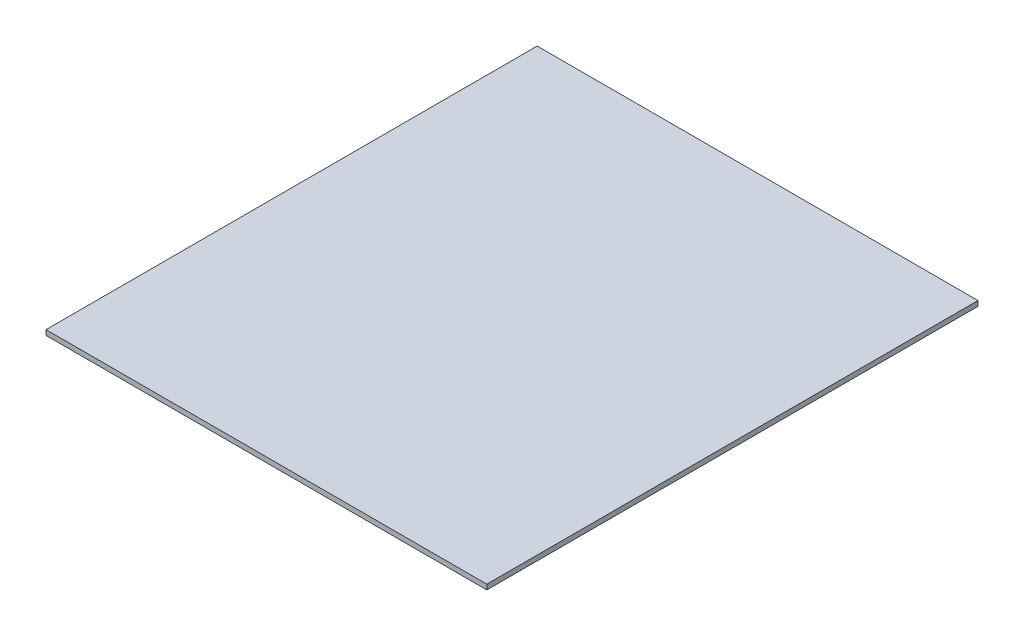
SolidWorks part; units mm, degrees
ref_plane "Front Plane" through (0, 0, 0) normal (0, 0, 1) x (1, 0, 0)
ref_plane "Top Plane" through (0, 0, 0) normal (0, 1, 0) x (1, 0, 0)
ref_plane "Right Plane" through (0, 0, 0) normal (1, 0, 0) x (0, 0, -1)
sketch "Sketch1" plane through (0, 0, 0) normal (0, 1, 0) x (1, 0, 0)
  line L1 (-175, 195) -> (175, 195)
  line L2 (-175, 195) -> (-175, -195)
  line L3 (-175, -195) -> (175, -195)
  line L4 (175, 195) -> (175, -195)
  line L5 (-175, 195) -> (175, -195) construction
  line L6 (-175, -195) -> (175, 195) construction
  point P0 (0, 0)
  dimension "D1" = 390
  dimension "D2" = 350
extrude "Boss-Extrude1" add sketch "Sketch1" along normal mid plane 4
